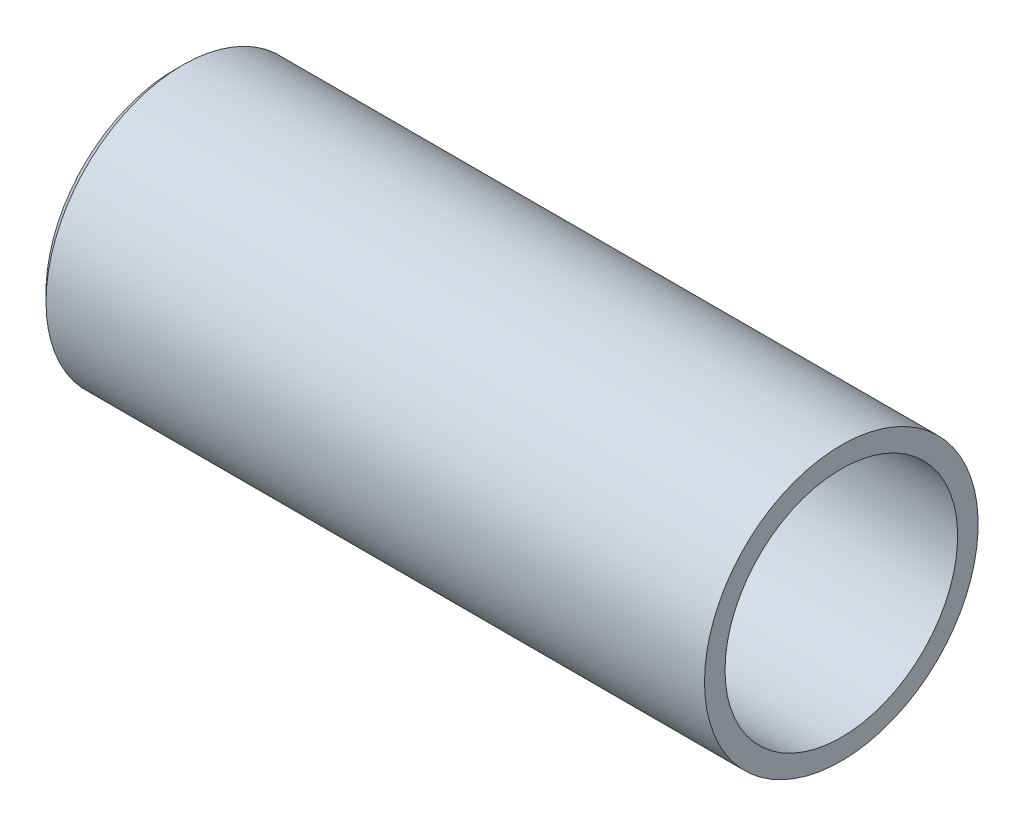
SolidWorks part; units mm, degrees
material "不锈钢 (铁素体)"
ref_plane "前视基准面" through (0, 0, 0) normal (0, 0, 1) x (1, 0, 0)
ref_plane "上视基准面" through (0, 0, 0) normal (0, 1, 0) x (1, 0, 0)
ref_plane "右视基准面" through (0, 0, 0) normal (1, 0, 0) x (0, 0, -1)
sketch "草图2" plane through (0, 17.5552, 0) normal (0, 0, 1) x (1, 0, 0)
  line L1 (1.6724, 14.6209) -> (40.6724, 14.6209)
  line L2 (1.6724, 14.6209) -> (1.6724, 6.6209)
  line L3 (1.6724, 6.6209) -> (40.6724, 6.6209)
  line L4 (40.6724, 14.6209) -> (40.6724, 6.6209)
  dimension "D1" = 39
  dimension "D2" = 8
revolve "旋转2" add sketch "草图2" angle 360 about L3
shell "抽壳4" thickness 1.2
chamfer "倒角2" distance 0.5 angle 45 2 edges at (1.6724, 24.1761, 8) (2.8724, 24.1761, -6.8)
equation "\"1.2.00mm\"=10"
